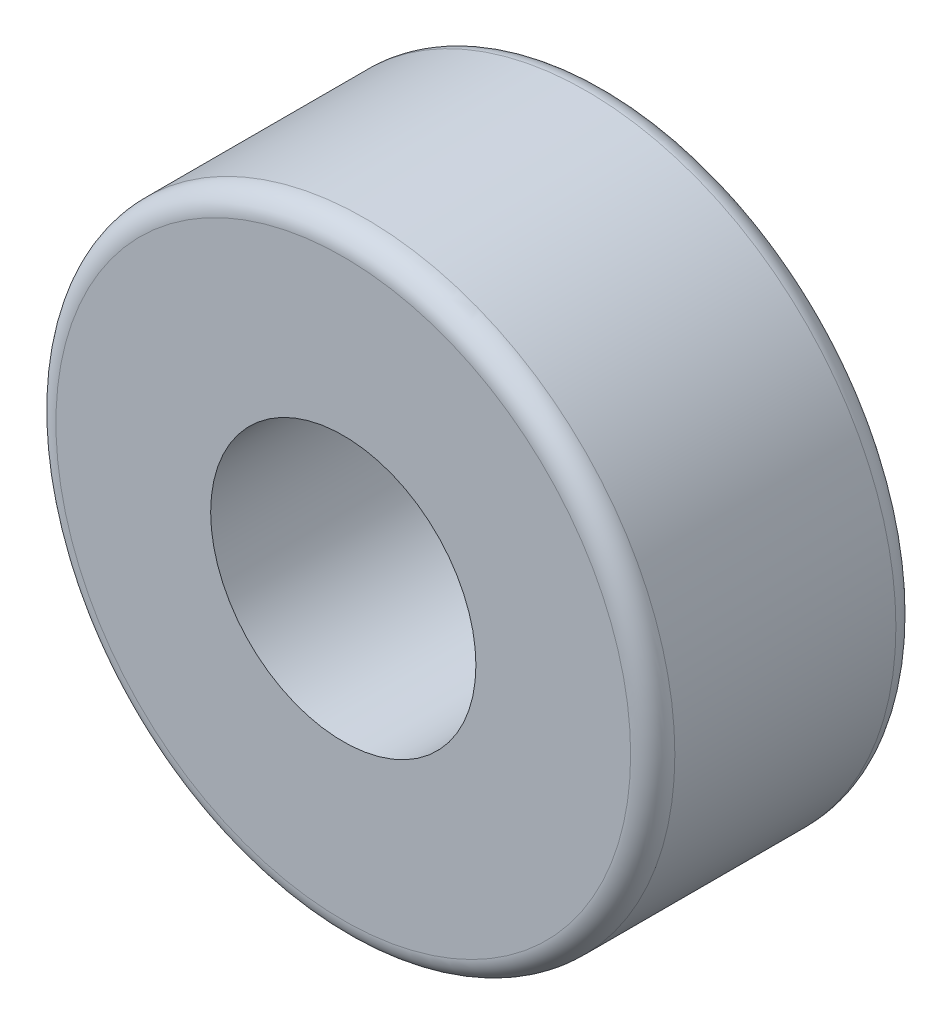
SolidWorks part; units mm, degrees
ref_plane "Plano frontal" through (0, 0, 0) normal (0, 0, 1) x (1, 0, 0)
ref_plane "Plano superior" through (0, 0, 0) normal (0, 1, 0) x (1, 0, 0)
ref_plane "Plano direito" through (0, 0, 0) normal (1, 0, 0) x (0, 0, -1)
sketch "Esboço1" plane through (0, 0, 0) normal (0, 0, 1) x (1, 0, 0)
  circle A0 centre (0, 0.2911) radius 3
  circle A1 centre (0, 0.2911) radius 7
  dimension "D1" = 6
  dimension "D2" = 14
extrude "Ressalto-extrusão1" add sketch "Esboço1" along normal blind 6
fillet "Filete1" radius 0.5 2 edges at (7, 0.2911, 0) (7, 0.2911, 6)
